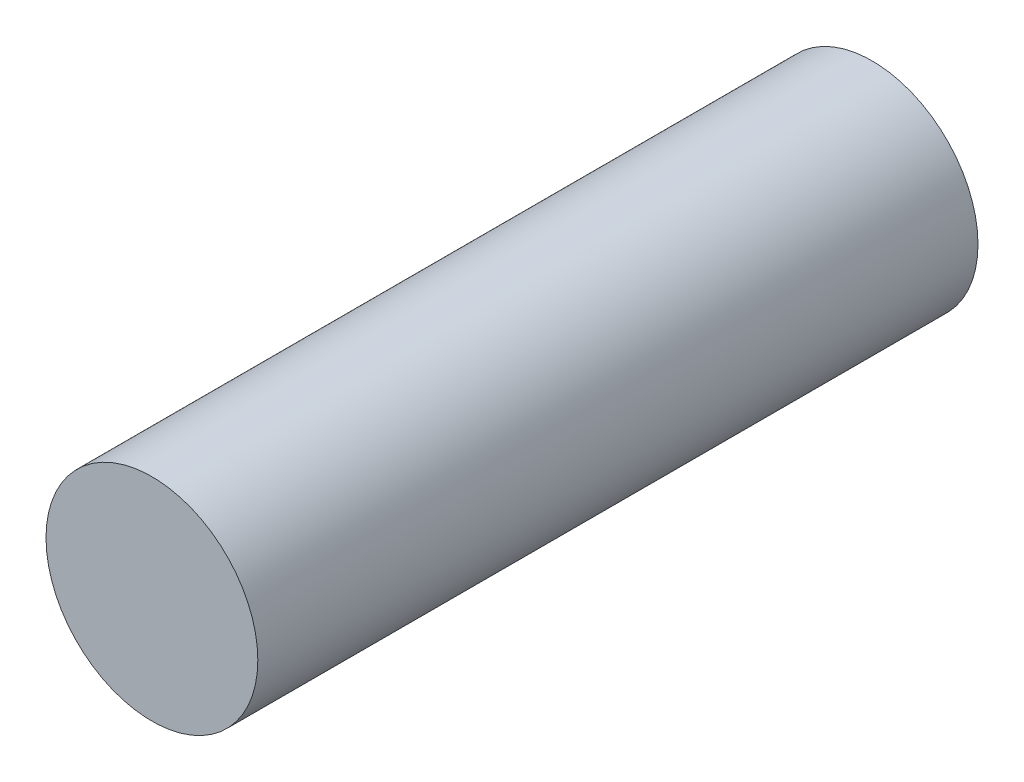
SolidWorks part; units mm, degrees
ref_plane "Płaszczyzna przednia" through (0, 0, 0) normal (0, 0, 1) x (1, 0, 0)
ref_plane "Płaszczyzna górna" through (0, 0, 0) normal (0, 1, 0) x (1, 0, 0)
ref_plane "Płaszczyzna prawa" through (0, 0, 0) normal (1, 0, 0) x (0, 0, -1)
sketch "Sketch1" plane through (0, 0, 0) normal (0, 0, 1) x (1, 0, 0)
  circle A0 centre (0, 0) radius 5
  dimension "D1" = 10
extrude "Boss-Extrude1" add sketch "Sketch1" along normal blind 34
